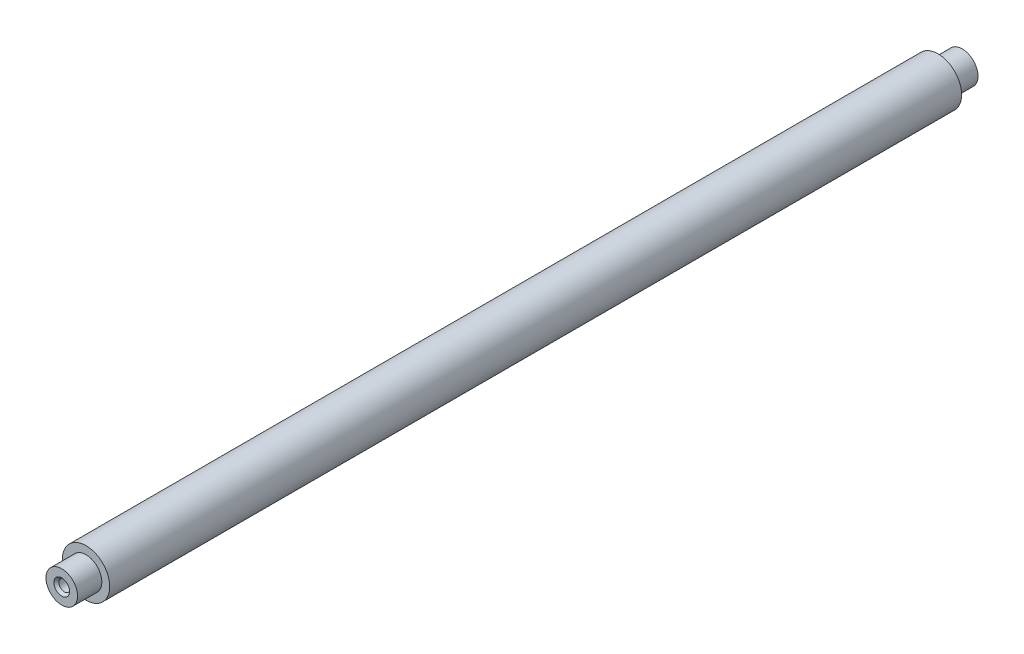
SolidWorks part; units mm, degrees
ref_plane "Front" through (0, 0, 0) normal (0, 0, 1) x (1, 0, 0)
ref_plane "Top" through (0, 0, 0) normal (0, 1, 0) x (1, 0, 0)
ref_plane "Right" through (0, 0, 0) normal (1, 0, 0) x (0, 0, -1)
sketch "Sketch1" plane through (0, 0, 0) normal (0, 0, 1) x (1, 0, 0)
  circle A0 centre (0, 0) radius 9.525
  dimension "D1" = 19.05
extrude "Boss-Extrude1" add sketch "Sketch1" along normal blind 342.9
sketch "Sketch2" plane through (0, 0, 342.9) normal (0, 0, 1) x (1, 0, 0)
  circle A0 centre (0, 0) radius 6.35
  dimension "D1" = 12.7
extrude "Boss-Extrude2" add sketch "Sketch2" along normal blind 9.779
hole_wizard "#12-24 Tapped Hole1" positions "Sketch3" profile "Sketch4" tap size "#12-24" standard "ANSI Inch"
sketch "Sketch3" plane through (0, 0, 352.679) normal (0, 0, 1) x (1, 0, 0)
  point P0 (0, 0)
sketch "Sketch4" plane through (0, 0, 352.679) normal (1, 0, 0) x (0, -1, 0)
  line L0 (0, 0) -> (0, 26.7507)
  line L1 (0, 26.7507) -> (2.2479, 25.4)
  line L2 (2.2479, 25.4) -> (2.2479, 1.0665)
  line L3 (2.2479, 1.0665) -> (3.175, 0)
  line L5 (3.175, 0) -> (0, 0)
  line L6 (-2.2479, 1.0665) -> (-3.175, 0) construction
  line L10 (0, 26.7507) -> (-2.2479, 25.4) construction
  line L11 (0, -6.35) -> (0, 107.95) construction
  dimension "Tap Drill Dia." = 4.4958
  dimension "Tap Drill Depth" = 25.4
  dimension "Near C'Sink Dia." = 6.35
  dimension "Near C'Sink Angle" = 82
  dimension "Drill Angle" = 118
sketch "Sketch5" plane through (0, 0, 0) normal (0, 0, -1) x (-1, 0, 0)
  circle A0 centre (0, 0) radius 6.35
  dimension "D1" = 12.7
extrude "Boss-Extrude3" add sketch "Sketch5" along normal blind 9.779
hole_wizard "#12-24 Tapped Hole2" positions "Sketch6" profile "Sketch7" tap size "#12-24" standard "ANSI Inch"
sketch "Sketch6" plane through (0, 0, -9.779) normal (0, 0, -1) x (-1, 0, 0)
  point P0 (0, 0)
sketch "Sketch7" plane through (0, 0, -9.779) normal (1, 0, 0) x (0, 1, 0)
  line L0 (0, 0) -> (0, 26.7507)
  line L1 (0, 26.7507) -> (2.2479, 25.4)
  line L2 (2.2479, 25.4) -> (2.2479, 1.0665)
  line L3 (2.2479, 1.0665) -> (3.175, 0)
  line L5 (3.175, 0) -> (0, 0)
  line L6 (-2.2479, 1.0665) -> (-3.175, 0) construction
  line L10 (0, 26.7507) -> (-2.2479, 25.4) construction
  line L11 (0, -6.35) -> (0, 107.95) construction
  dimension "Tap Drill Dia." = 4.4958
  dimension "Tap Drill Depth" = 25.4
  dimension "Near C'Sink Dia." = 6.35
  dimension "Near C'Sink Angle" = 82
  dimension "Drill Angle" = 118
